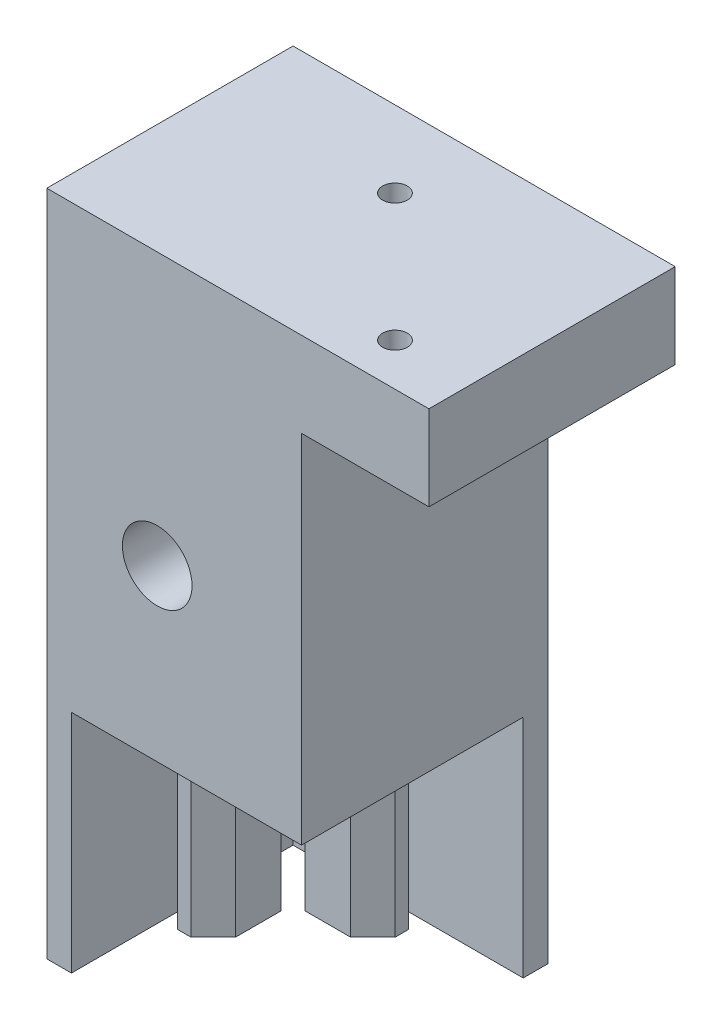
SolidWorks part; units mm, degrees
ref_plane "前视基准面" through (0, 0, 0) normal (0, 0, 1) x (1, 0, 0)
ref_plane "上视基准面" through (0, 0, 0) normal (0, 1, 0) x (1, 0, 0)
ref_plane "右视基准面" through (0, 0, 0) normal (1, 0, 0) x (0, 0, -1)
other "Configuration Table"
sketch "草图1" plane through (0, 0, 0) normal (0, 1, 0) x (1, 0, 0)
  line L1 (0, 0) -> (30, 0)
  line L2 (0, 0) -> (0, 23)
  line L3 (0, 23) -> (30, 23)
  line L4 (30, 0) -> (30, 23)
  dimension "D1" = 30
  dimension "D2" = 23
extrude "凸台-拉伸1" add sketch "草图1" along normal blind 72
sketch "草图2" plane through (0, 0, 0) normal (0, -1, 0) x (1, 0, 0)
  line L1 (30, 0) -> (3, 0)
  line L2 (30, 0) -> (30, -20)
  line L3 (30, -20) -> (3, -20)
  line L4 (3, 0) -> (3, -20)
  dimension "D1" = 20
  dimension "D2" = 27
extrude "切除-拉伸1" cut sketch "草图2" against normal blind 20
sketch "草图3" plane through (0, 0, 0) normal (0, 0, 1) x (1, 0, 0)
  line L0 (3, 20) -> (30, 20) construction
  line L1 (0, 72) -> (0, 0) construction
  circle A0 centre (13, 40) radius 4.1
  dimension "D1" = 8.2
  dimension "D2" = 20
  dimension "D3" = 13
extrude "切除-拉伸2" cut sketch "草图3" against normal blind 6
sketch "草图7" plane through (0, 0, -23) normal (0, 0, -1) x (-1, 0, 0)
  line L0 (-30, 72) -> (-30, 0) construction
  line L1 (-30, 72) -> (-45, 72)
  line L2 (-30, 72) -> (-30, 62)
  line L3 (-30, 62) -> (-45, 62)
  line L4 (-45, 72) -> (-45, 62)
  line L5 (-45, 29) -> (-45, 61) construction
  line L8 (-30, 72) -> (0, 72) construction
  dimension "D1" = 10
extrude "凸台-拉伸2" add sketch "草图7" against normal up to surface (23 mm away) up to face at (17.1, 40, 0)
sketch "草图8" plane through (0, 72, 0) normal (0, 1, 0) x (1, 0, 0)
  line L0 (45, 23) -> (0, 23) construction
  line L4 (0, 23) -> (0, 0) construction
  circle A0 centre (21, 18) radius 1.4
  circle A1 centre (33, 5) radius 1.4
  dimension "D1" = 2.8
  dimension "D2" = 2.8
  dimension "D3" = 21
  dimension "D4" = 12
  dimension "D5" = 13
  dimension "D6" = 5
sketch "草图9" plane through (0, 20, 0) normal (0, -1, 0) x (1, 0, 0)
  line L11 (16.1, -19.5) -> (16.1, -18.5) construction
  line L15 (16.1, -20) -> (16.1, -18.5)
  line L16 (16.1, -18.5) -> (18.5, -18.5)
  line L17 (18.5, -18.5) -> (18.5, -16.65)
  line L18 (18.5, -16.65) -> (15.75, -13.9)
  line L19 (15.75, -13.9) -> (10.25, -13.9)
  line L20 (10.25, -13.9) -> (7.5, -16.65)
  line L21 (7.5, -16.65) -> (7.5, -18.5)
  line L22 (7.5, -16.65) -> (7.5, -18.5) construction
  line L23 (7.5, -18.5) -> (9.9, -18.5)
  line L24 (9.9, -18.5) -> (9.9, -20)
  line L30 (3, -20) -> (30, -20) construction
  line L31 (15.9, -20) -> (15.9, -18.3)
  line L32 (15.9, -18.3) -> (18.3, -18.3)
  line L33 (18.3, -18.3) -> (18.3, -16.7328)
  line L34 (18.3, -16.7328) -> (15.6672, -14.1)
  line L35 (15.6672, -14.1) -> (10.3328, -14.1)
  line L36 (10.3328, -14.1) -> (7.7, -16.7328)
  line L37 (7.7, -16.7328) -> (7.7, -18.3)
  line L38 (7.7, -18.3) -> (10.1, -18.3)
  line L39 (10.1, -18.3) -> (10.1, -20)
  line L40 (10.1, -20) -> (15.9, -20)
  line M8 (3, -20) -> (30, -20)
  dimension "D1" = 0.2
extrude "凸台-拉伸3" add sketch "草图9" along normal up to surface (20 mm away) contours L38 L39 L31 L32 L33 L34 L35 L36 L37 M8 up to face at (11, 0, -14.3333)
ref_plane "基准面1" through (11.5, 0, -11.5) normal (0.7071, 0, -0.7071) x (-0.7071, 0, -0.7071)
mirror "镜向1" about plane through (11.5, 0, -11.5) normal (0.7071, 0, -0.7071) of "凸台-拉伸3"
sketch "草图11" plane through (0, 0, 0) normal (0, 0, 1) x (1, 0, 0)
  line L8 (0, 0) -> (3, 0)
  line L9 (3, 0) -> (3, 20)
  line L10 (3, 20) -> (30, 20)
  line L11 (30, 20) -> (30, 62)
  line L12 (30, 62) -> (45, 62)
  line L13 (45, 62) -> (45, 72)
  line L14 (45, 72) -> (0, 72)
  line L15 (0, 72) -> (0, 0)
  line L16 (0, 0) -> (3, 0)
  line L17 (3, 0) -> (3, 20)
  line L18 (3, 20) -> (30, 20)
  line L19 (30, 20) -> (30, 62)
  line L20 (30, 62) -> (45, 62)
  line L21 (45, 62) -> (45, 72)
  line L22 (45, 72) -> (0, 72)
  line L23 (0, 72) -> (0, 0)
  circle A1 centre (13, 40) radius 4.1
  circle A2 centre (13, 40) radius 4.1
  dimension "D2" = 0
  dimension "D1" = 0
extrude "凸台-拉伸5" add sketch "草图11" along normal blind 6
sketch "草图12" plane through (0, 72, 0) normal (0, 1, 0) x (1, 0, 0)
  line L0 (45, 23) -> (0, 23) construction
  line L1 (0, 23) -> (0, -6) construction
  circle A0 centre (21, 14) radius 1.45
  circle A1 centre (36, -1) radius 1.45
  dimension "D1" = 2.9
  dimension "D2" = 2.9
  dimension "D3" = 15
  dimension "D4" = 15
  dimension "D5" = 9
  dimension "D6" = 21
extrude "切除-拉伸3" cut sketch "草图12" against normal blind 5
sketch "草图13" plane through (0, 67, 0) normal (0, 1, 0) x (1, 0, 0)
  circle A1 centre (21, 14) radius 1.45
  circle A2 centre (21, 14) radius 1.45
  dimension "D1" = 0
extrude "切除-拉伸4" cut sketch "草图13" against normal blind 1.5
sketch "草图14" plane through (0, 0, 0) normal (0, -1, 0) x (1, 0, 0)
  line L52 (3, 6) -> (3, -7.1) construction
  line L53 (30, -20) -> (15.9, -20)
  line L54 (30, -20) -> (30, -20.1)
  line L55 (30, -20.1) -> (15.9, -20.1)
  line L56 (15.9, -20) -> (15.9, -20.1)
  line L57 (10.1, -20) -> (3, -20)
  line L58 (10.1, -20) -> (10.1, -20.1)
  line L59 (10.1, -20.1) -> (3, -20.1)
  line L60 (3, -20) -> (3, -20.1)
  line L61 (3, -12.9) -> (2.9, -12.9)
  line L62 (3, -12.9) -> (3, -20.1)
  line L63 (3, -20.1) -> (2.9, -20.1)
  line L64 (2.9, -12.9) -> (2.9, -20.1)
  line L65 (3, -7.1) -> (2.9, -7.1)
  line L66 (3, -7.1) -> (3, 6)
  line L67 (3, 6) -> (2.9, 6)
  line L68 (2.9, -7.1) -> (2.9, 6)
  line L69 (0, 6) -> (3, 6) construction
  line M5 (10.1, -20) -> (3, -20)
  line M6 (3, -20) -> (3, -12.9)
  line M16 (3, -7.1) -> (3, 6)
  line M17 (3, 6) -> (0, 6)
  line M20 (30, -23) -> (30, -20)
  line M21 (30, -20) -> (15.9, -20)
  dimension "D1" = 0.1
  dimension "D2" = 0.1
  dimension "D3" = 0.1
  dimension "D4" = 0.1
extrude "切除-拉伸5" cut sketch "草图14" along direction (0, 1, 0) on the side against the normal up to surface (20 mm away) contours L60 L59 L58 M5 | L61 L64 L63 L60 M6 | L56 L55 M21 M20 | L68 L65 M16 M17
sketch "草图15" plane through (0, 0, 0) normal (0, -1, 0) x (1, 0, 0)
  line L26 (4.7, -7.1) -> (2.9, -7.1)
  line L27 (2.9, -7.1) -> (2.9, 6)
  line L28 (2.9, 6) -> (0, 6)
  line L29 (0, 6) -> (0, -23)
  line L30 (0, -23) -> (30, -23)
  line L31 (30, -23) -> (30, -20.1)
  line L32 (30, -20.1) -> (15.9, -20.1)
  line L33 (15.9, -20.1) -> (15.9, -18.3)
  line L34 (15.9, -18.3) -> (18.3, -18.3)
  line L35 (18.3, -18.3) -> (18.3, -16.7328)
  line L36 (18.3, -16.7328) -> (15.6672, -14.1)
  line L37 (15.6672, -14.1) -> (10.3328, -14.1)
  line L38 (10.3328, -14.1) -> (7.7, -16.7328)
  line L39 (7.7, -16.7328) -> (7.7, -18.3)
  line L40 (7.7, -18.3) -> (10.1, -18.3)
  line L41 (10.1, -18.3) -> (10.1, -20.1)
  line L42 (10.1, -20.1) -> (2.9, -20.1)
  line L43 (2.9, -20.1) -> (2.9, -12.9)
  line L44 (2.9, -12.9) -> (4.7, -12.9)
  line L45 (4.7, -12.9) -> (4.7, -15.3)
  line L46 (4.7, -15.3) -> (6.2672, -15.3)
  line L47 (6.2672, -15.3) -> (8.9, -12.6672)
  line L48 (8.9, -12.6672) -> (8.9, -7.3328)
  line L49 (8.9, -7.3328) -> (6.2672, -4.7)
  line L50 (6.2672, -4.7) -> (4.7, -4.7)
  line L51 (4.7, -4.7) -> (4.7, -7.1)
  line L52 (4.7, -7.1) -> (2.9, -7.1)
  line L53 (2.9, -7.1) -> (2.9, 6)
  line L54 (2.9, 6) -> (0, 6)
  line L55 (0, 6) -> (0, -23)
  line L56 (0, -23) -> (30, -23)
  line L57 (30, -23) -> (30, -20.1)
  line L58 (30, -20.1) -> (15.9, -20.1)
  line L59 (15.9, -20.1) -> (15.9, -18.3)
  line L60 (15.9, -18.3) -> (18.3, -18.3)
  line L61 (18.3, -18.3) -> (18.3, -16.7328)
  line L62 (18.3, -16.7328) -> (15.6672, -14.1)
  line L63 (15.6672, -14.1) -> (10.3328, -14.1)
  line L64 (10.3328, -14.1) -> (7.7, -16.7328)
  line L65 (7.7, -16.7328) -> (7.7, -18.3)
  line L66 (7.7, -18.3) -> (10.1, -18.3)
  line L67 (10.1, -18.3) -> (10.1, -20.1)
  line L68 (10.1, -20.1) -> (2.9, -20.1)
  line L69 (2.9, -20.1) -> (2.9, -12.9)
  line L70 (2.9, -12.9) -> (4.7, -12.9)
  line L71 (4.7, -12.9) -> (4.7, -15.3)
  line L72 (4.7, -15.3) -> (6.2672, -15.3)
  line L73 (6.2672, -15.3) -> (8.9, -12.6672)
  line L74 (8.9, -12.6672) -> (8.9, -7.3328)
  line L75 (8.9, -7.3328) -> (6.2672, -4.7)
  line L76 (6.2672, -4.7) -> (4.7, -4.7)
  line L77 (4.7, -4.7) -> (4.7, -7.1)
  dimension "D1" = 0
extrude "凸台-拉伸6" add sketch "草图15" along normal blind 6.6
